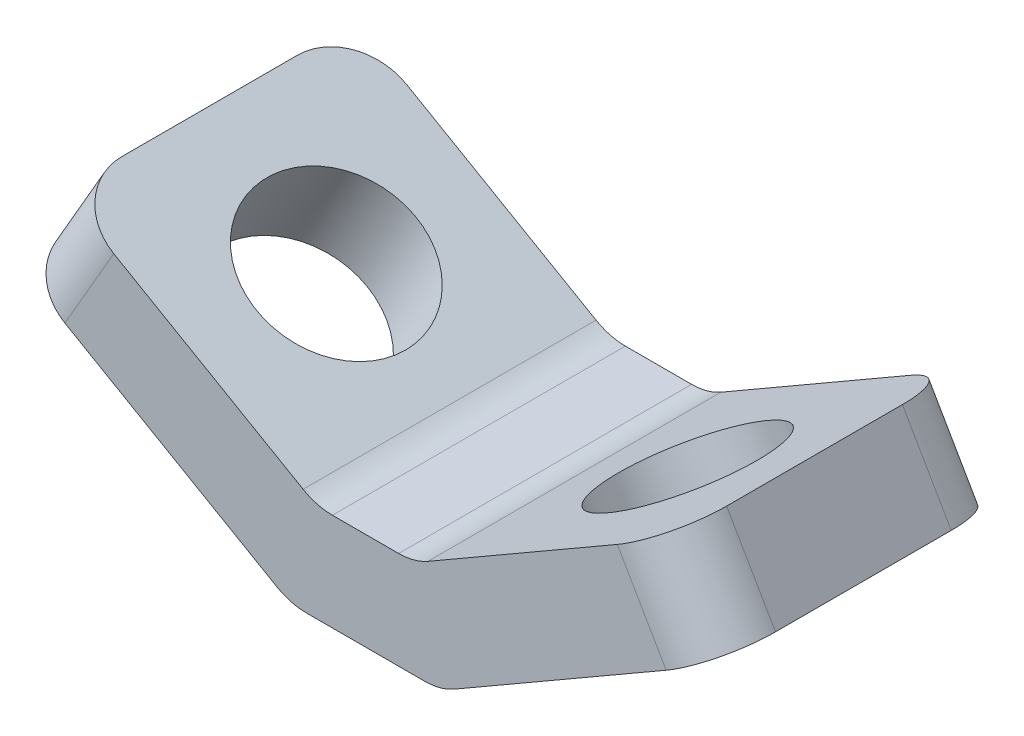
SolidWorks part; units mm, degrees
ref_plane "正面" through (0, 0, 0) normal (0, 0, 1) x (1, 0, 0)
ref_plane "平面" through (0, 0, 0) normal (0, 1, 0) x (1, 0, 0)
ref_plane "右側面" through (0, 0, 0) normal (1, 0, 0) x (0, 0, -1)
sketch "ｽｹｯﾁ1" plane through (0, 0, 0) normal (0, 0, 1) x (1, 0, 0)
  line L0 (0, 0) -> (-14.1506, 8.1699)
  line L1 (-14.1506, 8.1699) -> (-11.6506, 12.5)
  line L2 (-11.6506, 12.5) -> (1.3397, 5)
  line L3 (1.3397, 5) -> (6.3397, 5)
  line L4 (6.3397, 5) -> (19.3301, 12.5)
  line L5 (19.3301, 12.5) -> (21.8301, 8.1699)
  line L6 (21.8301, 8.1699) -> (7.6795, 0)
  line L7 (7.6795, 0) -> (0, 0)
  dimension "D1" = 150
  dimension "D2" = 150
  dimension "D3" = 5
  dimension "D4" = 5
  dimension "D5" = 5
  dimension "D6" = 15
  dimension "D7" = 15
  dimension "D8" = 5
extrude "ﾎﾞｽ - 押し出し1" add sketch "ｽｹｯﾁ1" along normal mid plane 15
sketch "ｽｹｯﾁ2" plane through (0, 0, 0) normal (-0.5, -0.866, 0) x (0, 0, 1)
  line L0 (7.5, 1.3397) -> (7.5, 16.3397) construction
  circle A0 centre (0, 8.8397) radius 4.1
  point P6 (7.5, 8.8397)
  dimension "D1" = 8.2
extrude "ｶｯﾄ - 押し出し1" cut sketch "ｽｹｯﾁ2" against normal through all both and the other way through all
sketch "ｽｹｯﾁ3" plane through (1.9199, -3.3253, 0) normal (0.5, -0.866, 0) x (0, 0, -1)
  line L0 (-7.5, 22.9904) -> (-7.5, 7.9904) construction
  line L1 (-7.5, 22.9904) -> (7.5, 22.9904) construction
  circle A0 centre (0, 15.4904) radius 4.1
  point P4 (-7.5, 15.4904)
  point P7 (0, 22.9904)
  dimension "D1" = 8.2
extrude "ｶｯﾄ - 押し出し2" cut sketch "ｽｹｯﾁ3" against normal through all both and the other way through all
fillet "ﾌｨﾚｯﾄ1" radius 3 8 edges at (20.5801, 10.3349, -7.5) (20.5801, 10.3349, 7.5) (-12.9006, 10.3349, -7.5) (-12.9006, 10.3349, 7.5) (7.6795, 0, 0) (0, 0, 0) (6.3397, 5, 0) (1.3397, 5, 0)
equation "\"D4@ｽｹｯﾁ1\"=\"D3@ｽｹｯﾁ1\""
equation "\"D5@ｽｹｯﾁ1\"=\"D3@ｽｹｯﾁ1\""
equation "\"D2@ｽｹｯﾁ1\"=\"D1@ｽｹｯﾁ1\""
